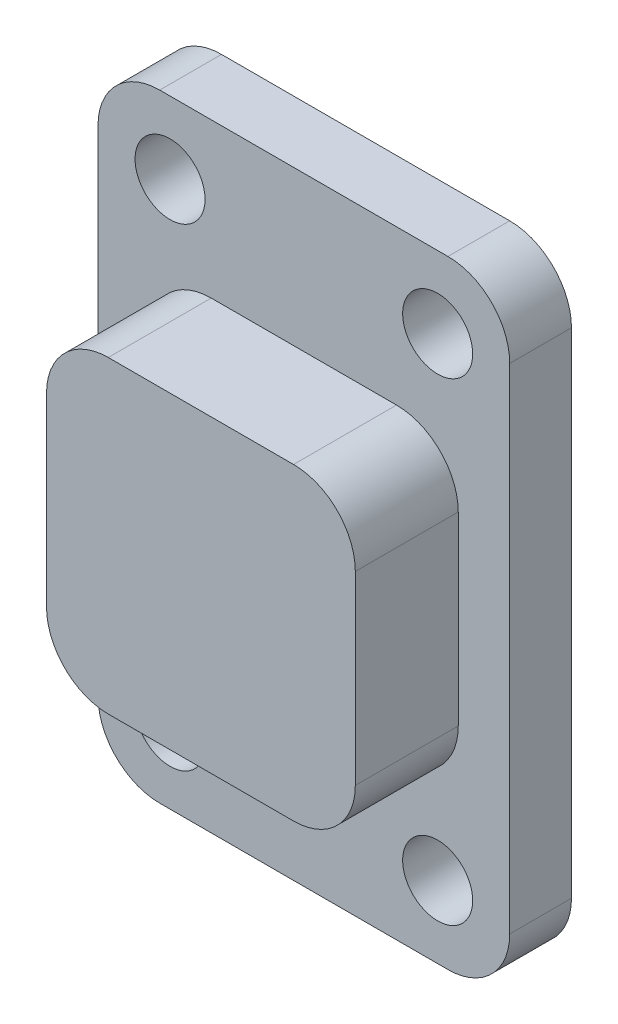
SolidWorks part; units mm, degrees
ref_plane "Front Plane" through (0, 0, 0) normal (0, 0, 1) x (1, 0, 0)
ref_plane "Top Plane" through (0, 0, 0) normal (0, 1, 0) x (1, 0, 0)
ref_plane "Right Plane" through (0, 0, 0) normal (1, 0, 0) x (0, 0, -1)
sketch "Sketch1" plane through (0, 0, 0) normal (0, 0, 1) x (1, 0, 0)
  line L1 (-10, -15) -> (10, -15)
  line L2 (-10, -15) -> (-10, 15)
  line L3 (-10, 15) -> (10, 15)
  line L4 (10, -15) -> (10, 15)
  line L5 (-10, -15) -> (10, 15) construction
  line L6 (-10, 15) -> (10, -15) construction
  point P0 (0, 0)
  dimension "D1" = 30
  dimension "D2" = 20
extrude "Boss-Extrude1" add sketch "Sketch1" along normal blind 3
sketch "Sketch2" plane through (0, 0, 3) normal (0, 0, 1) x (1, 0, 0)
  ellipse E0 centre (0, 0) end of major axis (0, 10) minor radius 5
  ellipse E1 centre (0, 0) end of major axis (0, 9) minor radius 4
  dimension "D1" = 5
  dimension "D2" = 10
  dimension "D3" = 4
  dimension "D4" = 9
extrude "Boss-Extrude2" [suppressed] add sketch "Sketch2" along normal blind 13
hole_wizard "Ø3.4 (3.4) Diameter Hole1" positions "Sketch4" profile "Sketch3" hole size "Ø3.4" standard "ANSI Metric" end condition through all
sketch "Sketch4" plane through (0, 0, 3) normal (0, 0, 1) x (1, 0, 0)
  line L0 (-10, 15) -> (-10, -15) construction
  line L1 (10, 15) -> (-10, 15) construction
  line L2 (10, -15) -> (10, 15) construction
  line L3 (-10, -15) -> (10, -15) construction
  point P0 (-6.5, 11.5)
  point P2 (6.5, 11.5)
  point P4 (6.5, -11.5)
  point P6 (-6.5, -11.5)
  dimension "D1" = 3.5
  dimension "D2" = 3.5
  dimension "D3" = 3.5
  dimension "D4" = 3.5
  dimension "D5" = 3.5
  dimension "D6" = 3.5
  dimension "D7" = 3.5
  dimension "D8" = 3.5
sketch "Sketch3" plane through (-6.5, 11.5, 3) normal (1, 0, 0) x (0, -1, 0)
  line L0 (0, 0) -> (0, 3)
  line L1 (0, 3) -> (1.7, 3)
  line L2 (1.7, 3) -> (1.7, 0)
  line L5 (1.7, 0) -> (0, 0)
  line L11 (0, -6.35) -> (0, 107.95) construction
  dimension "Thru Hole Dia." = 3.4
  dimension "Thru Hole Depth" = 3
sketch "Sketch5" plane through (0, 0, 0) normal (0, 0, -1) x (-1, 0, 0)
  circle A0 centre (0, 0) radius 3.4
extrude "Cut-Extrude1" cut sketch "Sketch5" against normal blind 0.5
fillet "Fillet1" radius 3 4 edges at (-10, -15, 1.5) (10, -15, 1.5) (10, 15, 1.5) (-10, 15, 1.5)
sketch "Sketch7" plane through (0, 0, 3) normal (0, 0, 1) x (1, 0, 0)
  line L1 (4, -7.5) -> (-4, -7.5)
  line L2 (4, -7.5) -> (4, 7.5)
  line L3 (4, 7.5) -> (-4, 7.5)
  line L4 (-4, -7.5) -> (-4, 7.5)
  line L5 (4, -7.5) -> (-4, 7.5) construction
  line L6 (4, 7.5) -> (-4, -7.5) construction
  point P0 (0, 0)
  dimension "D1" = 8
  dimension "D2" = 15
extrude "Boss-Extrude3" add sketch "Sketch7" along normal blind 11
sketch "Sketch8" plane through (4, 0, 0) normal (1, 0, 0) x (0, 0, -1)
  line L0 (-14, -7.5) -> (-14, -7) construction
  line L1 (-14, -7.5) -> (-14, 7.5) construction
  line L2 (-14, -7) -> (-13.134, -7.5)
  line L3 (-14, -7.5) -> (-3, -7.5) construction
  line L4 (-13.134, -7.5) -> (-13.134, 7.5) construction
  line L5 (-14, 7.5) -> (-3, 7.5) construction
  line L6 (-14, -7) -> (-13.134, -6.5)
  line L7 (-14, -6) -> (-13.134, -6.5)
  line L8 (-14, -6) -> (-13.134, -5.5)
  line L9 (-14, -5) -> (-13.134, -5.5)
  line L10 (-14, -5) -> (-13.134, -4.5)
  line L11 (-14, -4) -> (-13.134, -4.5)
  line L12 (-14, -4) -> (-13.134, -3.5)
  line L13 (-14, -3) -> (-13.134, -3.5)
  line L14 (-14, -3) -> (-13.134, -2.5)
  line L15 (-14, -2) -> (-13.134, -2.5)
  line L16 (-14, -2) -> (-13.134, -1.5)
  line L17 (-14, -1) -> (-13.134, -1.5)
  line L18 (-14, -1) -> (-13.134, -0.5)
  line L19 (-14, 0) -> (-13.134, -0.5)
  line L20 (-14, 0) -> (-13.134, 0.5)
  line L21 (-14, 1) -> (-13.134, 0.5)
  line L22 (-14, 1) -> (-13.134, 1.5)
  line L23 (-14, 2) -> (-13.134, 1.5)
  line L24 (-14, 2) -> (-13.134, 2.5)
  line L25 (-14, 3) -> (-13.134, 2.5)
  line L26 (-14, 3) -> (-13.134, 3.5)
  line L27 (-14, 4) -> (-13.134, 3.5)
  line L28 (-14, 4) -> (-13.134, 4.5)
  line L29 (-14, 5) -> (-13.134, 4.5)
  line L30 (-14, 5) -> (-13.134, 5.5)
  line L31 (-14, 6) -> (-13.134, 5.5)
  line L32 (-14, 6) -> (-13.134, 6.5)
  line L33 (-14, 7) -> (-13.134, 6.5)
  line L34 (-14, 7) -> (-13.134, 7.5)
  dimension "D1" = 0.5
  dimension "D2" = 60
  dimension "D3" = 60
  dimension "D4" = 15
extrude "Cut-Extrude3" cut sketch "Sketch8" against normal through all and the other way through all
sketch "Sketch11" plane through (0, 0, 3) normal (0, 0, 1) x (1, 0, 0)
  circle A0 centre (0, 0) radius 2.5
  dimension "D1" = 5
extrude "Cut-Extrude4" cut sketch "Sketch11" along normal through all flip side to cut
sketch "Sketch12" plane through (10, 0, 0) normal (1, 0, 0) x (0, 0, -1)
  line L1 (-3, -12) -> (-3, 12) construction
  line L2 (-15.4302, 10.4417) -> (-8, 10.4417)
  line L3 (-15.4302, 10.4417) -> (-15.4302, -10.6669)
  line L4 (-15.4302, -10.6669) -> (-8, -10.6669)
  line L5 (-8, 10.4417) -> (-8, -10.6669)
  dimension "D1" = 5
extrude "Cut-Extrude5" cut sketch "Sketch12" against normal through all
sketch "Sketch13" plane through (0, 0, 0) normal (0, 0, -1) x (-1, 0, 0)
  circle A0 centre (0, 0) radius 2.75
  circle A1 centre (0, 0) radius 3.4
  dimension "D1" = 5.5
extrude "Boss-Extrude4" add sketch "Sketch13" against normal up to surface (0.5 mm away) up to face at (-3.4, 0, 0.5)
sketch "Sketch14" plane through (0, 0, 3) normal (0, 0, 1) x (1, 0, 0)
  line L1 (7.5, -7.5) -> (-7.5, -7.5)
  line L2 (7.5, -7.5) -> (7.5, 7.5)
  line L3 (7.5, 7.5) -> (-7.5, 7.5)
  line L4 (-7.5, -7.5) -> (-7.5, 7.5)
  line L5 (7.5, -7.5) -> (-7.5, 7.5) construction
  line L6 (7.5, 7.5) -> (-7.5, -7.5) construction
  point P0 (0, 0)
  dimension "D1" = 15
extrude "Boss-Extrude5" add sketch "Sketch14" along normal up to surface (5 mm away) up to face at (0, 2.5, 8)
fillet "Fillet2" radius 3 4 edges at (7.5, -7.5, 5.5) (7.5, 7.5, 5.5) (-7.5, 7.5, 5.5) (-7.5, -7.5, 5.5)
